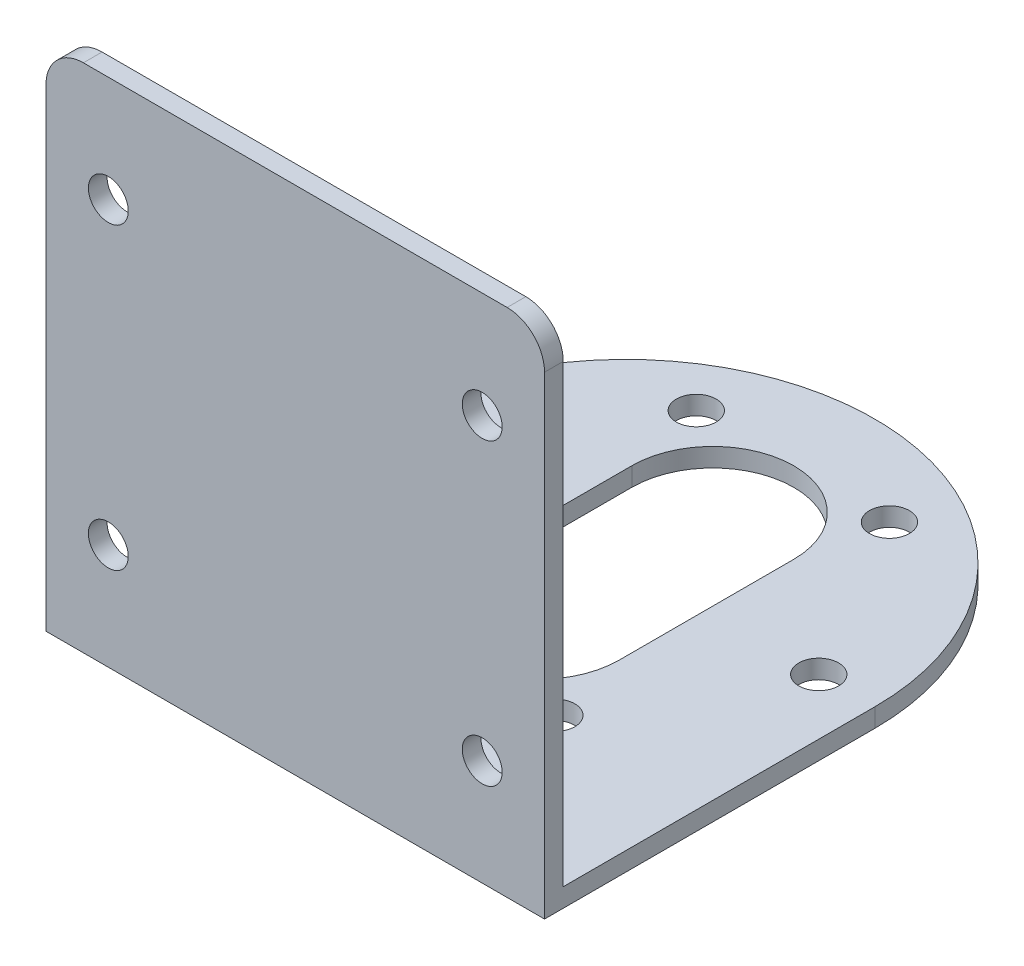
SolidWorks part; units mm, degrees
ref_plane "前视基准面" through (0, 0, 0) normal (0, 0, 1) x (1, 0, 0)
ref_plane "上视基准面" through (0, 0, 0) normal (0, 1, 0) x (1, 0, 0)
ref_plane "右视基准面" through (0, 0, 0) normal (1, 0, 0) x (0, 0, -1)
other "Configuration Table"
sketch "草图1" plane through (0, 0, 0) normal (0, 1, 0) x (1, 0, 0)
  line L0 (-6.5, 20.25) -> (-6.5, 6.25)
  line L1 (-20, -13.25) -> (20, -13.25)
  line L2 (-20, -13.25) -> (-20, 13.25)
  line L4 (20, -13.25) -> (20, 13.25)
  line L5 (-20, -13.25) -> (20, 13.25) construction
  line L6 (-20, 13.25) -> (20, -13.25) construction
  line L7 (6.5, 20.25) -> (6.5, 6.25)
  line L8 (-6.5, 13.25) -> (6.5, 13.25) construction
  arc A0 (20, 13.25) -> (-20, 13.25) centre (0, 13.25) ccw
  arc A1 (6.5, 20.25) -> (-6.5, 20.25) centre (0, 20.25) ccw
  arc A2 (6.5, 6.25) -> (-6.5, 6.25) centre (0, 6.25) cw
  circle A3 centre (15.5, 13.25) radius 1.6
  circle A4 centre (7.75, -0.1734) radius 1.6
  circle A5 centre (-7.75, -0.1734) radius 1.6
  circle A6 centre (-15.5, 13.25) radius 1.6
  circle A7 centre (-7.75, 26.6734) radius 1.6
  circle A8 centre (7.75, 26.6734) radius 1.6
  point P0 (0, 0)
  point P14 (7.4632, 24.4839)
  point P19 (0, 0)
  point P29 (0, 13.25)
  dimension "D4" = 6.5
  dimension "D7" = 3.2
  dimension "D1" = 40
  dimension "D2" = 26.5
  dimension "D3" = 14
  dimension "D6" = 15.5
  dimension "D5" = 6
extrude "凸台-拉伸1" add sketch "草图1" along normal blind 1.5
sketch "草图3" plane through (0, 1.5, 0) normal (0, 1, 0) x (1, 0, 0)
  line L0 (20, -13.25) -> (20, 13.25) construction
  line L1 (-20, -13.25) -> (20, -13.25)
  line L2 (-20, -13.25) -> (-20, -11.75)
  line L3 (-20, -11.75) -> (20, -11.75)
  line L4 (20, -13.25) -> (20, -11.75)
  dimension "D1" = 1.5
extrude "凸台-拉伸2" add sketch "草图3" along normal blind 39.5
sketch "草图4" plane through (0, 0, 13.25) normal (0, 0, 1) x (1, 0, 0)
  line L0 (-20, 20.5) -> (22.9236, 20.5) construction
  line L1 (0, 0) -> (0, 41.7064) construction
  line L2 (-20, 41) -> (-20, 0) construction
  line L4 (-20, 0) -> (20, 0)
  line L5 (20, 0) -> (20, 41)
  line L6 (20, 41) -> (-20, 41)
  line L7 (-20, 41) -> (-20, 0)
  line L8 (-20, 0) -> (20, 0) construction
  line L9 (20, 0) -> (20, 41) construction
  line L10 (20, 41) -> (-20, 41) construction
  line L11 (-20, 41) -> (-20, 0) construction
  circle A0 centre (-15, 32.5) radius 1.6
  circle A1 centre (15, 32.5) radius 1.6
  circle A2 centre (15, 8.5) radius 1.6
  circle A3 centre (-15, 8.5) radius 1.6
  point P19 (0, 0)
  dimension "D4" = 3.2
  dimension "D2" = 24
  dimension "D3" = 30
  dimension "D1" = 0
extrude "切除-拉伸1" cut sketch "草图4" against normal up to next
fillet "圆角1" radius 3 2 edges at (-20, 41, 12.5) (20, 41, 12.5)
